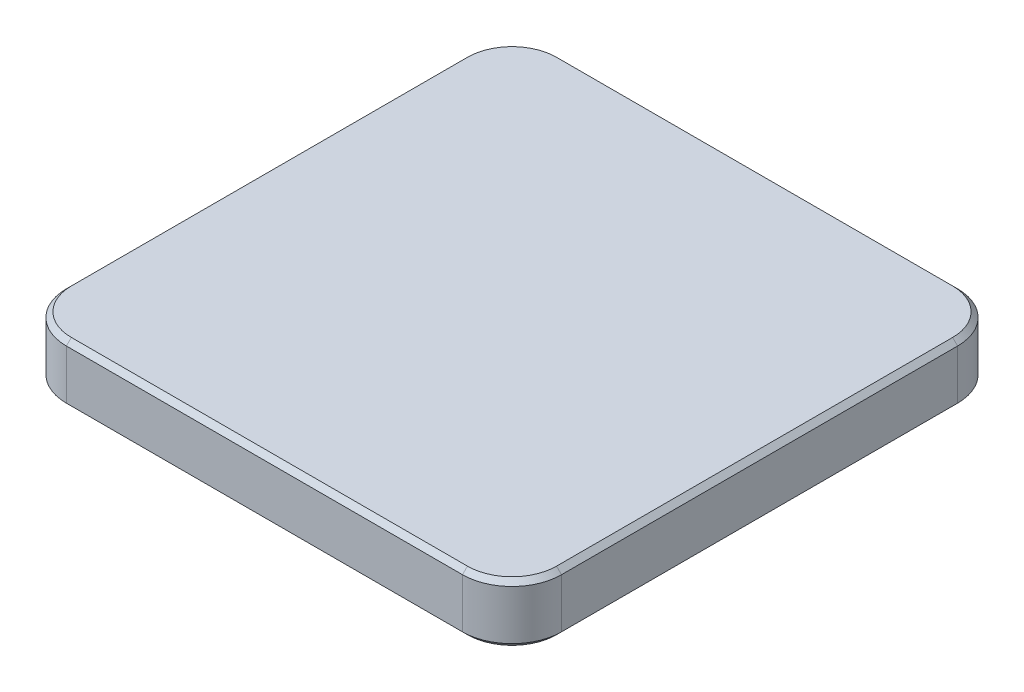
SolidWorks part; units mm, degrees
ref_plane "前基準面" through (0, 0, 0) normal (0, 0, 1) x (1, 0, 0)
ref_plane "上基準面" through (0, 0, 0) normal (0, 1, 0) x (1, 0, 0)
ref_plane "右基準面" through (0, 0, 0) normal (1, 0, 0) x (0, 0, -1)
ref_plane "平面1"
sketch "草圖1" plane through (0, 0, 0) normal (0, 1, 0) x (-1, 0, 0)
  line L0 (50, -50) -> (-50, -50)
  line L1 (-50, -50) -> (-50, 50)
  line L2 (-50, 50) -> (50, 50)
  line L3 (50, 50) -> (50, -50)
  dimension "D1" = 100
  dimension "D2" = 100
extrude "擠出1" add sketch "草圖1" along normal blind 12
fillet "圓角1" radius 10 4 edges at (-50, 6, 50) (50, 6, -50) (-50, 6, -50) (50, 6, 50)
chamfer "倒角1" distance 1 distance2 1 16 edges at (47.0711, 12, 47.0711) (0, 12, 50) (-47.0711, 12, 47.0711) (-50, 12, 0) (-47.0711, 12, -47.0711) (0, 12, -50) (47.0711, 12, -47.0711) (50, 12, 0) (47.0711, 0, 47.0711) (50, 0, 0) (47.0711, 0, -47.0711) (0, 0, -50) (-47.0711, 0, -47.0711) (-50, 0, 0) (-47.0711, 0, 47.0711) (0, 0, 50)
